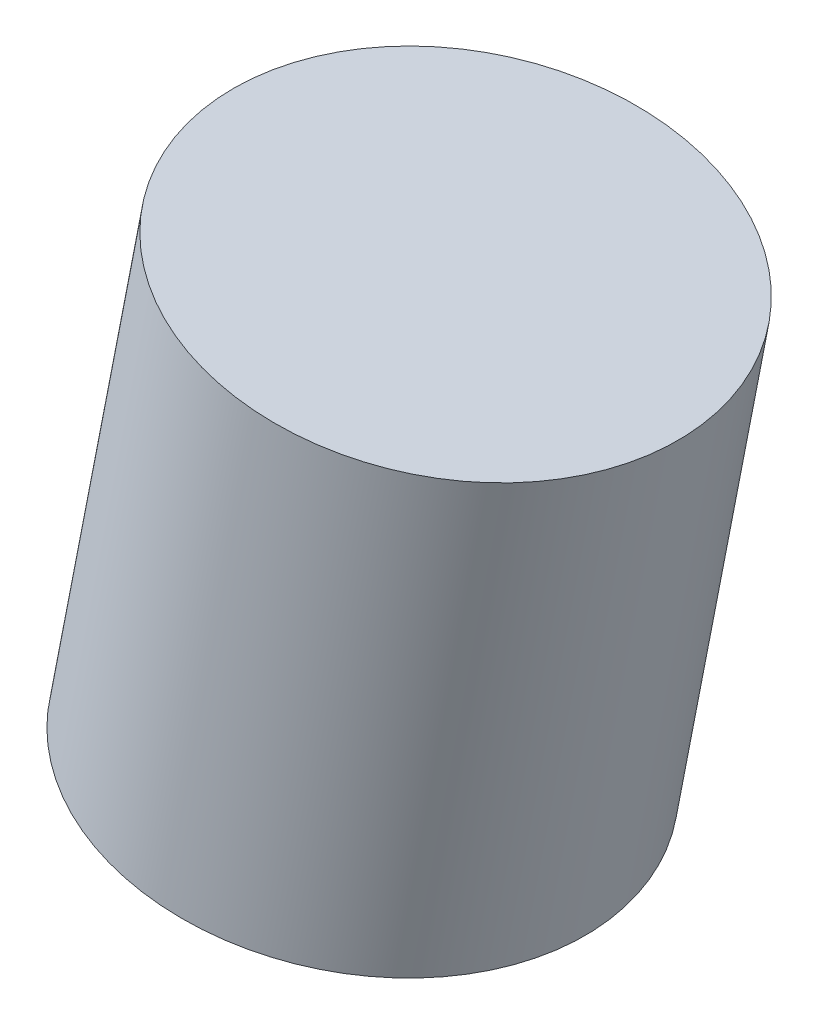
SolidWorks part; units mm, degrees
ref_plane "前视基准面" through (0, 0, 0) normal (0, 0, 1) x (1, 0, 0)
ref_plane "上视基准面" through (0, 0, 0) normal (0, 1, 0) x (1, 0, 0)
ref_plane "右视基准面" through (0, 0, 0) normal (1, 0, 0) x (0, 0, -1)
other "Configuration Table"
sketch "草图3" plane through (-12.1378, -63.7373, 0.4005) normal (0.1871, 0.9823, -0.0062) x (-0.9773, 0.1855, -0.1025)
  circle A0 centre (-25, -30) radius 7.5
  dimension "D1" = 15
extrude "凸台-拉伸1" add sketch "草图3" along normal blind 16
